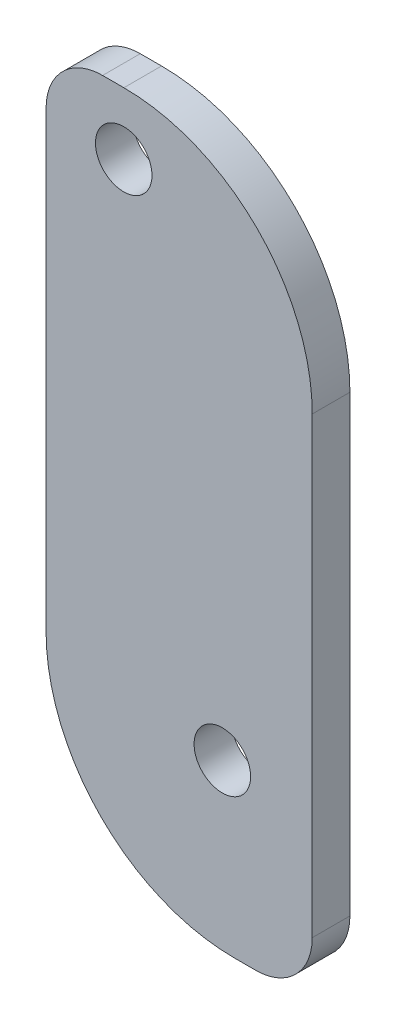
SolidWorks part; units mm, degrees
ref_plane "Plano frontal" through (0, 0, 0) normal (0, 0, 1) x (1, 0, 0)
ref_plane "Plano superior" through (0, 0, 0) normal (0, 1, 0) x (1, 0, 0)
ref_plane "Plano direito" through (0, 0, 0) normal (1, 0, 0) x (0, 0, -1)
sketch "Esboço1" plane through (0, 0, 0) normal (0, 0, 1) x (1, 0, 0)
  line L0 (0, 0) -> (0, -25.562) construction
  line L1 (0, 0) -> (5.2361, -25.02) construction
  line L5 (-1.121, 3.2913) -> (0.0087, 3.2913)
  line L6 (-4.121, 0.2913) -> (-4.121, -23.7856)
  line L7 (5.879, -33.7856) -> (7.0087, -33.7856)
  line L8 (10.0087, -6.7087) -> (10.0087, -30.7856)
  circle A0 centre (0, 0) radius 1.5
  circle A1 centre (5.2361, -25.02) radius 1.5
  arc A4 (0.0087, 3.2913) -> (10.0087, -6.7087) centre (0.0087, -6.7087) cw
  arc A5 (-4.121, -23.7856) -> (5.879, -33.7856) centre (5.879, -23.7856) ccw
  arc A6 (-1.121, 3.2913) -> (-4.121, 0.2913) centre (-1.121, 0.2913) ccw
  arc A7 (7.0087, -33.7856) -> (10.0087, -30.7856) centre (7.0087, -30.7856) ccw
  dimension "D2" = 3
  dimension "D3" = 10
  dimension "D4" = 3
  dimension "D1" = 11.82
extrude "Ressalto-extrusão1" add sketch "Esboço1" along normal blind 2
